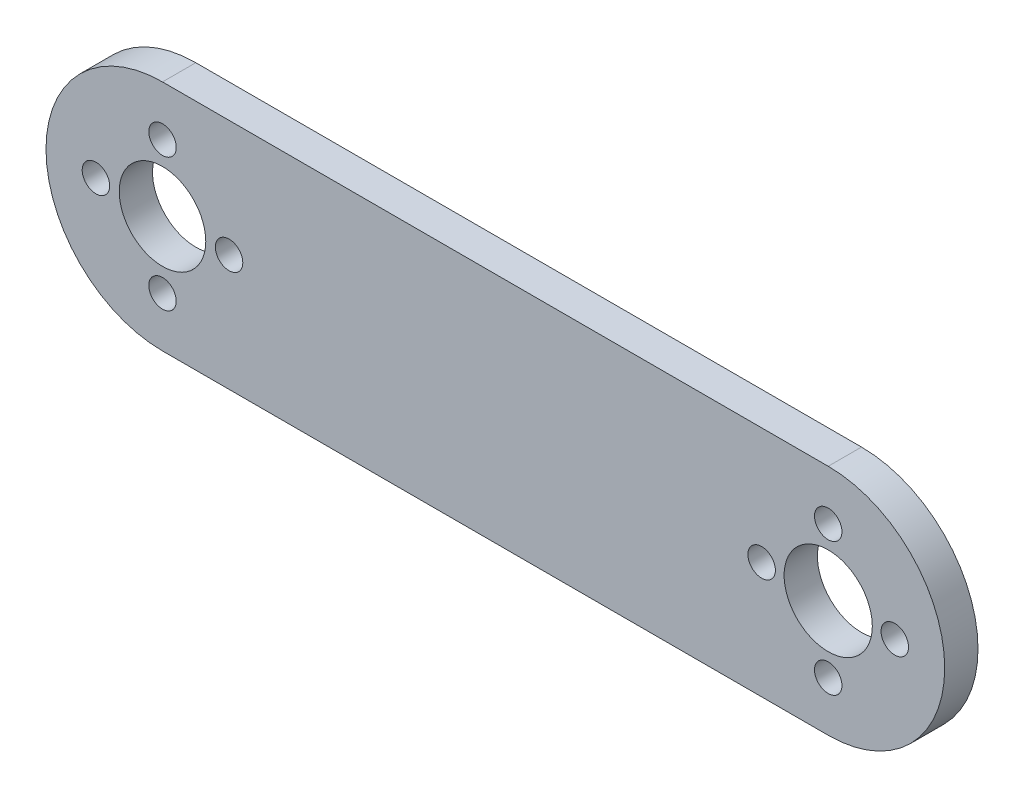
SolidWorks part; units mm, degrees
ref_plane "前视基准面" through (0, 0, 0) normal (0, 0, 1) x (1, 0, 0)
ref_plane "上视基准面" through (0, 0, 0) normal (0, 1, 0) x (1, 0, 0)
ref_plane "右视基准面" through (0, 0, 0) normal (1, 0, 0) x (0, 0, -1)
sketch "草图1" plane through (0, 0, 0) normal (0, 0, 1) x (1, 0, 0)
  line L0 (0, 14) -> (0, -14)
  line L1 (0, 14) -> (80, 14)
  line L2 (0, -14) -> (80, -14)
  line L3 (80, 14) -> (80, -14)
  circle A0 centre (0, 0) radius 8
  circle A1 centre (0, 0) radius 5.2
  circle A2 centre (8, 0) radius 1.65
  circle A3 centre (0, 8) radius 1.65
  circle A4 centre (0, -8) radius 1.65
  circle A5 centre (-8, 0) radius 1.65
  circle A6 centre (0, 0) radius 14
  circle A7 centre (72, 0) radius 1.65
  circle A8 centre (80, 0) radius 8
  circle A9 centre (80, 8) radius 1.65
  circle A10 centre (88, 0) radius 1.65
  circle A11 centre (80, 0) radius 5.3
  circle A12 centre (80, 0) radius 14
  circle A13 centre (80, -8) radius 1.65
extrude "凸台-拉伸1" add sketch "草图1" along normal blind 4 contours L0 A6 A4 A0 A5 A3 | A5 A0 A4 L0 A1 A3 | A4 A0 A2 A3 L0 A1 | L0 A6 A3 A0 A2 A4 | A13 L3 A12 A9 A8 A10 | A13 A8 A7 A9 L3 A12 | A13 L3 A11 A9 A8 A7 | A13 A8 A10 A9 L3 A11 | A12 L1 A6 L2
